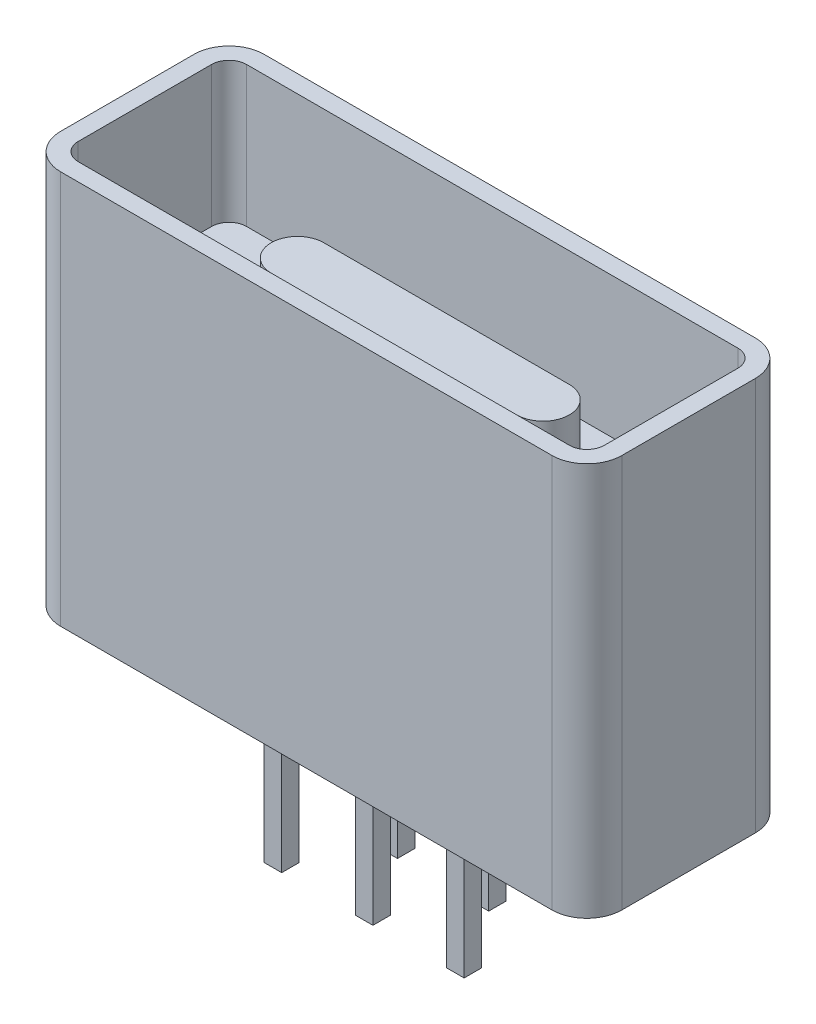
SolidWorks part; units mm, degrees
ref_plane "前视基准面" through (0, 0, 0) normal (0, 0, 1) x (1, 0, 0)
ref_plane "上视基准面" through (0, 0, 0) normal (0, 1, 0) x (1, 0, 0)
ref_plane "右视基准面" through (0, 0, 0) normal (1, 0, 0) x (0, 0, -1)
sketch "草图1" plane through (0, 0, 0) normal (0, 1, 0) x (1, 0, 0)
  line L0 (0, 50.7532) -> (0, -61.5721) construction
  line L1 (-4, 1.45) -> (4, 1.45)
  line L2 (-4, 1.45) -> (-4, -1.45)
  line L3 (-4, -1.45) -> (4, -1.45)
  line L4 (4, 1.45) -> (4, -1.45)
  line L5 (-61.5721, 0) -> (77.4822, 0) construction
  dimension "D1" = 8
  dimension "D2" = 2.9
extrude "凸台-拉伸1" add sketch "草图1" along normal blind 5.61
sketch "草图2" plane through (0, 0, 0) normal (0, -1, 0) x (1, 0, 0)
  line L0 (-4.8238, 0.5) -> (5.0262, 0.5) construction
  line L1 (0, 1.969) -> (0, -2.2322) construction
  line L2 (-1.3, 0.654) -> (-1.3, -0.8173) construction
  line L3 (-1.425, 0.625) -> (-1.175, 0.625)
  line L4 (-1.425, 0.625) -> (-1.425, 0.375)
  line L5 (-1.425, 0.375) -> (-1.175, 0.375)
  line L6 (-1.175, 0.625) -> (-1.175, 0.375)
  line L7 (1.3, 0.654) -> (1.3, -0.8173) construction
  line L8 (1.175, 0.625) -> (1.175, 0.375)
  line L9 (1.425, 0.375) -> (1.175, 0.375)
  line L10 (1.425, 0.625) -> (1.425, 0.375)
  line L11 (1.425, 0.625) -> (1.175, 0.625)
  line L12 (-4.3483, -0.5) -> (4.7535, -0.5) construction
  line L13 (-0.125, 0.625) -> (0.125, 0.625)
  line L14 (-0.125, 0.625) -> (-0.125, 0.375)
  line L15 (-0.125, 0.375) -> (0.125, 0.375)
  line L16 (0.125, 0.625) -> (0.125, 0.375)
  line L17 (-0.65, -0.1151) -> (-0.65, -0.9) construction
  line L18 (-0.775, -0.375) -> (-0.525, -0.375)
  line L19 (-0.775, -0.375) -> (-0.775, -0.625)
  line L20 (-0.775, -0.625) -> (-0.525, -0.625)
  line L21 (-0.525, -0.375) -> (-0.525, -0.625)
  line L22 (0.65, -0.1151) -> (0.65, -0.9) construction
  line L23 (4.3483, -0.5) -> (-4.7535, -0.5) construction
  line L24 (0.525, -0.375) -> (0.525, -0.625)
  line L25 (0.775, -0.625) -> (0.525, -0.625)
  line L26 (0.775, -0.375) -> (0.775, -0.625)
  line L27 (0.775, -0.375) -> (0.525, -0.375)
  dimension "D1" = 0.25
  dimension "D2" = 0.25
  dimension "D3" = 2.6
  dimension "D4" = 0.25
  dimension "D5" = 0.25
  dimension "D6" = 1
  dimension "D7" = 0.5
  dimension "D8" = 0.25
  dimension "D9" = 0.25
  dimension "D10" = 1.3
extrude "凸台-拉伸2" add sketch "草图2" along normal blind 2.29
fillet "圆角2" radius 0.5 4 edges at (4, 2.805, 1.45) (4, 2.805, -1.45) (-4, 2.805, -1.45) (-4, 2.805, 1.45)
sketch "草图3" plane through (0, 5.61, 0) normal (0, 1, 0) x (1, 0, 0)
  line L24 (3.75, -0.95) -> (3.75, 0.95)
  line L25 (-3.5, -1.2) -> (3.5, -1.2)
  line L26 (-3.75, 0.95) -> (-3.75, -0.95)
  line L27 (3.5, 1.2) -> (-3.5, 1.2)
  line L28 (3.75, -0.95) -> (3.75, 0.95)
  line L29 (-3.5, -1.2) -> (3.5, -1.2)
  line L30 (-3.75, 0.95) -> (-3.75, -0.95)
  line L31 (3.5, 1.2) -> (-3.5, 1.2)
  arc A20 (3.75, 0.95) -> (3.5, 1.2) centre (3.5, 0.95) ccw
  arc A21 (3.5, -1.2) -> (3.75, -0.95) centre (3.5, -0.95) ccw
  arc A22 (-3.75, -0.95) -> (-3.5, -1.2) centre (-3.5, -0.95) ccw
  arc A23 (-3.5, 1.2) -> (-3.75, 0.95) centre (-3.5, 0.95) ccw
  arc A24 (3.75, 0.95) -> (3.5, 1.2) centre (3.5, 0.95) ccw
  arc A25 (3.5, -1.2) -> (3.75, -0.95) centre (3.5, -0.95) ccw
  arc A26 (-3.75, -0.95) -> (-3.5, -1.2) centre (-3.5, -0.95) ccw
  arc A27 (-3.5, 1.2) -> (-3.75, 0.95) centre (-3.5, 0.95) ccw
  dimension "D1" = 0.25
extrude "切除-拉伸1" cut sketch "草图3" against normal blind 2
sketch "草图4" plane through (0, 3.61, 0) normal (0, 1, 0) x (1, 0, 0)
  line L0 (-1.75, 0.175) -> (1.75, 0.175) construction
  line L1 (-1.75, 0.55) -> (1.75, 0.55)
  line L2 (-1.75, -0.2) -> (1.75, -0.2)
  line L3 (0, 1.9724) -> (0, -2.2794) construction
  line L5 (-3.5, -1.2) -> (3.5, -1.2) construction
  arc A0 (-1.75, 0.55) -> (-1.75, -0.2) centre (-1.75, 0.175) ccw
  arc A1 (1.75, -0.2) -> (1.75, 0.55) centre (1.75, 0.175) ccw
  point P2 (0, 0.175)
  dimension "D1" = 3.5
  dimension "D2" = 0.75
  dimension "D3" = 1
extrude "凸台-拉伸3" add sketch "草图4" along normal blind 1
